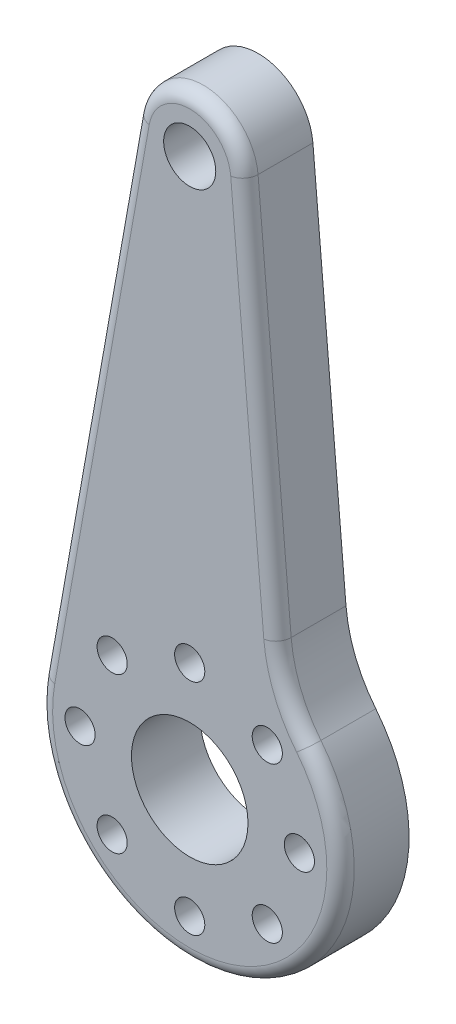
SolidWorks part; units mm, degrees
ref_plane "Front Plane" through (0, 0, 0) normal (0, 0, 1) x (1, 0, 0)
ref_plane "Top Plane" through (0, 0, 0) normal (0, 1, 0) x (1, 0, 0)
ref_plane "Right Plane" through (0, 0, 0) normal (1, 0, 0) x (0, 0, -1)
sketch "Sketch1" plane through (0, 0, 0) normal (0, 0, 1) x (1, 0, 0)
  line L0 (-18.9266, 20.3511) -> (-25.8186, -18.4239)
  line L3 (-11.0501, 20.3511) -> (-4.1581, -18.4239)
  line L4 (-14.9884, 0.8298) -> (-14.9884, 20.8298) construction
  line L5 (-14.6371, -20.3489) -> (49985.3629, -20.3489) construction
  circle A2 centre (-14.9884, 19.6511) radius 1.9
  circle A3 centre (-14.9884, -20.3489) radius 4.25
  arc A5 (-11.0501, 20.3511) -> (-18.9266, 20.3511) centre (-14.9884, 19.6511) ccw
  arc A6 (-25.8186, -18.4239) -> (-4.1581, -18.4239) centre (-14.9884, -20.3489) ccw
  circle A7 centre (-15.0314, -20.0888) radius 11 construction
  circle A8 centre (-6.9884, -20.3489) radius 1.1
  circle A9 centre (-9.3315, -26.0058) radius 1.1
  circle A10 centre (-14.9884, -28.3489) radius 1.1
  circle A11 centre (-20.6452, -26.0058) radius 1.1
  circle A12 centre (-22.9884, -20.3489) radius 1.1
  circle A13 centre (-20.6452, -14.692) radius 1.1
  circle A14 centre (-14.9884, -12.3489) radius 1.1
  circle A15 centre (-9.3315, -14.692) radius 1.1
  point P30 (-14.9884, -20.3489)
  dimension "D1" = 3.8
  dimension "D3" = 40
  dimension "D4" = 11
  dimension "D2" = 4
  dimension "D5" = 8.5
  dimension "D6" = 2.2
  dimension "D7" = 8
  dimension "D8" = 8
extrude "Boss-Extrude1" add sketch "Sketch1" along normal blind 5
sketch "Sketch2" plane through (0, 0, 5) normal (0, 0, 1) x (1, 0, 0)
  circle A0 centre (-14.9884, -20.3489) radius 11.5
  dimension "D1" = 23
extrude "Cut-Extrude1" [suppressed] cut sketch "Sketch2" against normal blind 1.75
sketch "Sketch5" plane through (0, 0, 5) normal (0, 0, 1) x (1, 0, 0)
  circle A2 centre (-14.8897, 3.8764) radius 1.55
  circle A3 centre (-14.8897, 3.8764) radius 8
extrude "Boss-Extrude2" [suppressed] add sketch "Sketch5" along normal blind 3
fillet "Fillet1" [suppressed] radius 1
sketch "Sketch4" plane through (0, 0, 0) normal (0, 0, -1) x (-1, 0, 0)
  circle A0 centre (22.9884, -20.3489) radius 1.75
  circle A1 centre (20.6452, -26.0058) radius 1.75
  circle A2 centre (14.9884, -28.3489) radius 1.75
  circle A3 centre (9.3315, -26.0058) radius 1.75
  circle A4 centre (6.9884, -20.3489) radius 1.75
  circle A5 centre (9.3315, -14.692) radius 1.75
  circle A6 centre (14.9884, -12.3489) radius 1.75
  circle A7 centre (20.6452, -14.692) radius 1.75
  circle A10 centre (14.9884, -20.3489) radius 4.25 construction
  point P20 (14.9884, -20.3489)
  dimension "D1" = 3.5
extrude "Cut-Extrude3" cut sketch "Sketch4" against normal blind 2.25
sketch "Croquis1" plane through (0, 0, 0) normal (0, 0, -1) x (-1, 0, 0)
  line L0 (11.0031, 19.9942) -> (8.28, -11.6312)
  line L1 (18.9266, 20.3511) -> (25.8186, -18.4239) construction
  line L2 (11.0501, 20.3511) -> (4.1581, -18.4239)
  arc A0 (11.0501, 20.3511) -> (11.0031, 19.9942) centre (14.9884, 19.6511) ccw
  arc A1 (4.1581, -18.4239) -> (8.28, -11.6312) centre (14.9884, -20.3489) cw
  dimension "D1" = 15
extrude "Cortar-Extruir1" cut sketch "Croquis1" against normal blind 10
fillet "Redondeo1" radius 10 1 edges at (-8.28, -11.6312, 2.5)
fillet "Redondeo3" radius 1 5 edges at (-14.8084, 23.647, 5) (-9.796, 5.9752, 5) (-7.9062, -10.9106, 5) (-12.2587, -31.0048, 5) (-22.3726, 0.9636, 5)
